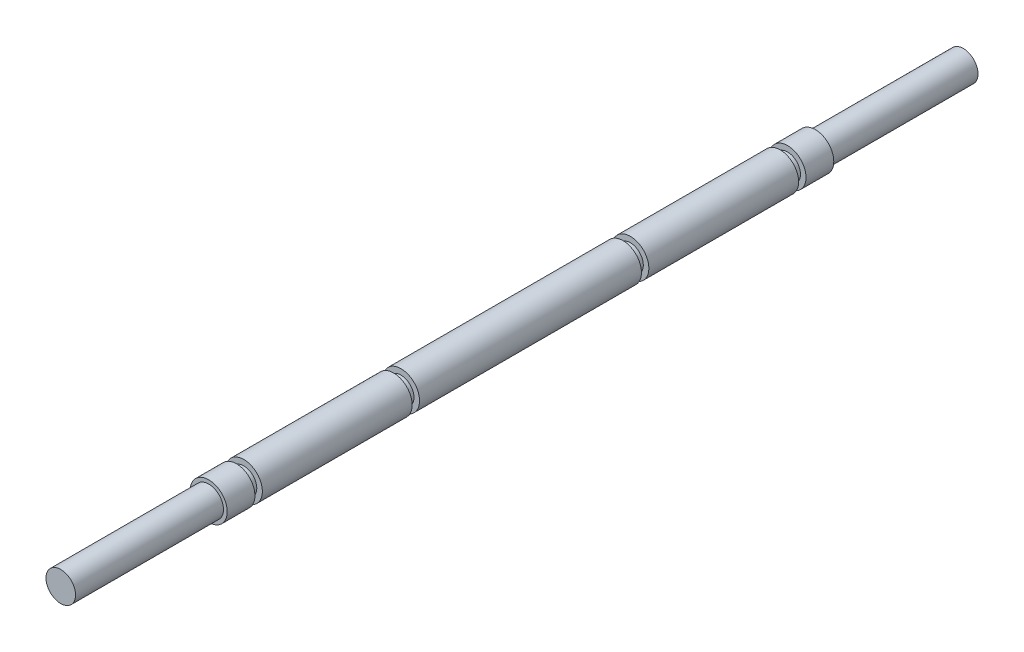
SolidWorks part; units mm, degrees
ref_plane "前视基准面" through (0, 0, 0) normal (0, 0, 1) x (1, 0, 0)
ref_plane "上视基准面" through (0, 0, 0) normal (0, 1, 0) x (1, 0, 0)
ref_plane "右视基准面" through (0, 0, 0) normal (1, 0, 0) x (0, 0, -1)
sketch "草图1" plane through (0, 0, 0) normal (0, 0, 1) x (1, 0, 0)
  circle A0 centre (0, 0) radius 5
  dimension "D1" = 10
extrude "凸台-拉伸1" add sketch "草图1" along normal blind 60
sketch "草图2" plane through (0, 0, 60) normal (0, 0, 1) x (1, 0, 0)
  circle A0 centre (0, 0) radius 3.5
  dimension "D1" = 7
extrude "凸台-拉伸2" add sketch "草图2" along normal blind 2
sketch "草图3" plane through (0, 0, 0) normal (0, 0, -1) x (-1, 0, 0)
  circle A0 centre (0, 0) radius 3.5
  dimension "D1" = 7
extrude "凸台-拉伸3" add sketch "草图3" along normal blind 2
sketch "草图4" plane through (0, 0, -2) normal (0, 0, -1) x (-1, 0, 0)
  circle A0 centre (0, 0) radius 5
  dimension "D1" = 10
extrude "凸台-拉伸4" add sketch "草图4" along normal blind 90
sketch "草图5" plane through (0, 0, 62) normal (0, 0, 1) x (1, 0, 0)
  circle A0 centre (0, 0) radius 5
  dimension "D1" = 10
extrude "凸台-拉伸5" add sketch "草图5" along normal blind 90
sketch "草图6" plane through (0, 0, 152) normal (0, 0, 1) x (1, 0, 0)
  circle A0 centre (0, 0) radius 4
  circle A1 centre (0, 0) radius 5
  circle M3 centre (0, 0) radius 5
  dimension "D1" = 8
  dimension "D2" = 10
extrude "切除-拉伸2" cut sketch "草图6" against normal blind 40 contours A0 M3
sketch "草图7" plane through (0, 0, -92) normal (0, 0, -1) x (-1, 0, 0)
  circle A0 centre (0, 0) radius 5
  circle A1 centre (0, 0) radius 4
  circle M1 centre (0, 0) radius 5
  dimension "D1" = 8
extrude "切除-拉伸3" cut sketch "草图7" against normal blind 40 contours A1 M1
ref_plane "基准面1" through (0, 0, -42.5) normal (0, 0, -1) x (-1, 0, 0)
sketch "草图8" plane through (0, 0, -42.5) normal (0, 0, -1) x (-1, 0, 0)
  circle A0 centre (0, 0) radius 5
  circle A1 centre (0, 0) radius 3.5
  dimension "D1" = 7
extrude "切除-拉伸4" cut sketch "草图8" along normal blind 2
ref_plane "基准面2" through (0, 0, 102.5) normal (0, 0, 1) x (1, 0, 0)
sketch "草图9" plane through (0, 0, 102.5) normal (0, 0, 1) x (1, 0, 0)
  circle A0 centre (0, 0) radius 5
  circle A1 centre (0, 0) radius 3.5
  dimension "D1" = 7
extrude "切除-拉伸5" cut sketch "草图9" along normal blind 2
